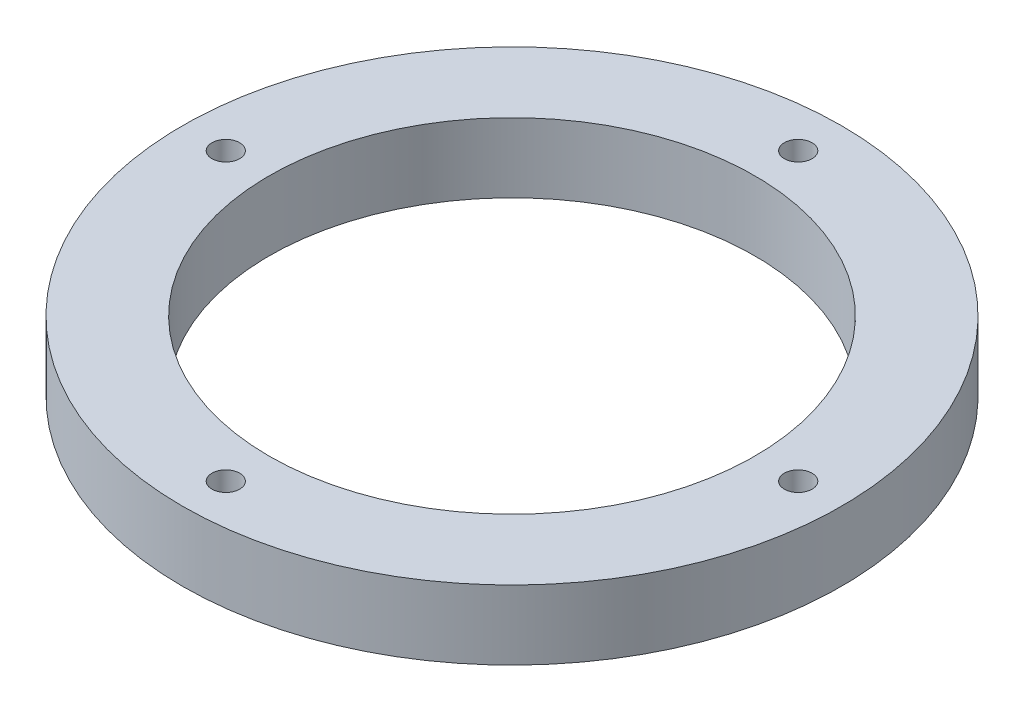
SolidWorks part; units mm, degrees
material "Alumina"
ref_plane "Front Plane" through (0, 0, 0) normal (0, 0, 1) x (1, 0, 0)
ref_plane "Top Plane" through (0, 0, 0) normal (0, 1, 0) x (1, 0, 0)
ref_plane "Right Plane" through (0, 0, 0) normal (1, 0, 0) x (0, 0, -1)
sketch "Sketch1" plane through (0, 0, 0) normal (0, 1, 0) x (1, 0, 0)
  circle A0 centre (0, 0) radius 47.5
  dimension "D1" = 95
extrude "Boss-Extrude1" add sketch "Sketch1" along normal blind 10
sketch "Sketch2" plane through (0, 10, 0) normal (0, 1, 0) x (1, 0, 0)
  circle A0 centre (0, 0) radius 35
  dimension "D1" = 70
extrude "Cut-Extrude1" cut sketch "Sketch2" against normal up to surface (10 mm away) up to face at (0, 0, 47.5)
sketch "Sketch3" plane through (0, 10, 0) normal (0, 1, 0) x (1, 0, 0)
  line L0 (0, 0) -> (0, 47.5) construction
  circle A0 centre (0, 0) radius 47.5 construction
  circle A1 centre (0, 41.25) radius 2
  dimension "D1" = 4
  dimension "D2" = 41.25
extrude "Cut-Extrude2" cut sketch "Sketch3" against normal up to surface (10 mm away) up to face at (0, 0, 35)
pattern_circular "CirPattern1" count 4 over 360 about axis through (0, 0, 0) along (0, 1, 0) of "Cut-Extrude2"
